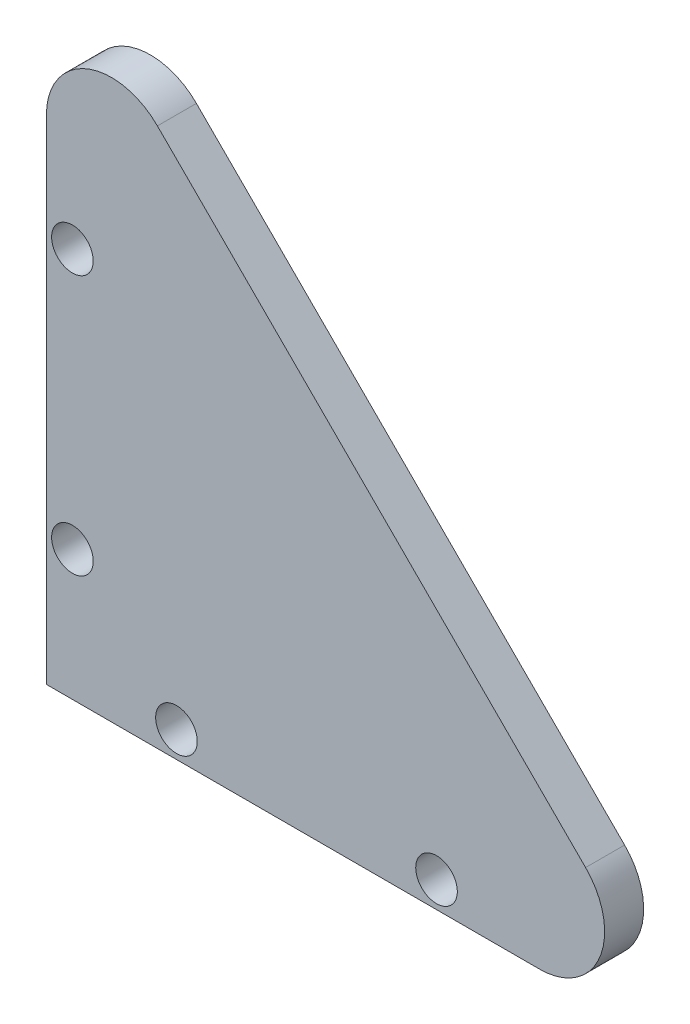
SolidWorks part; units mm, degrees
ref_plane "Plan de face" through (0, 0, 0) normal (0, 0, 1) x (1, 0, 0)
ref_plane "Plan de dessus" through (0, 0, 0) normal (0, 1, 0) x (1, 0, 0)
ref_plane "Plan de droite" through (0, 0, 0) normal (1, 0, 0) x (0, 0, -1)
sketch "Sketch1" plane through (0, 0, 0) normal (0, 0, 1) x (1, 0, 0)
  line L0 (-27.9172, 22.6563) -> (-27.9172, -27.3437)
  line L1 (-27.9172, -27.3437) -> (22.0828, -27.3437)
  line L2 (-27.9172, 22.6563) -> (22.0828, -27.3437)
  dimension "D1" = 50
  dimension "D2" = 50
extrude "Boss-Extrude1" add sketch "Sketch1" along normal blind 3
sketch "Sketch2" plane through (0, 0, 3) normal (0, 0, 1) x (1, 0, 0)
  line L0 (-25.9172, 18.6931) -> (-25.9172, -24.7265) construction
  line L1 (-27.9172, 22.6563) -> (-27.9172, -27.3437) construction
  line L2 (-27.9172, -27.3437) -> (-2.9172, -2.3437) construction
  line L3 (22.0828, -27.3437) -> (-27.9172, 22.6563) construction
  circle A0 centre (-25.9172, -17.3437) radius 1.6
  circle A1 centre (-25.9172, 2.6563) radius 1.6
  circle A2 centre (-17.9172, -25.3437) radius 1.6
  circle A3 centre (2.0828, -25.3437) radius 1.6
  dimension "D2" = 20
  dimension "D3" = 20
  dimension "D4" = 3.2
  dimension "D5" = 3.2
  dimension "D1" = 2
extrude "Cut-Extrude1" cut sketch "Sketch2" against normal blind 3
fillet "Fillet2" radius 5 2 edges at (22.0828, -27.3437, 1.5) (-27.9172, 22.6563, 1.5)
